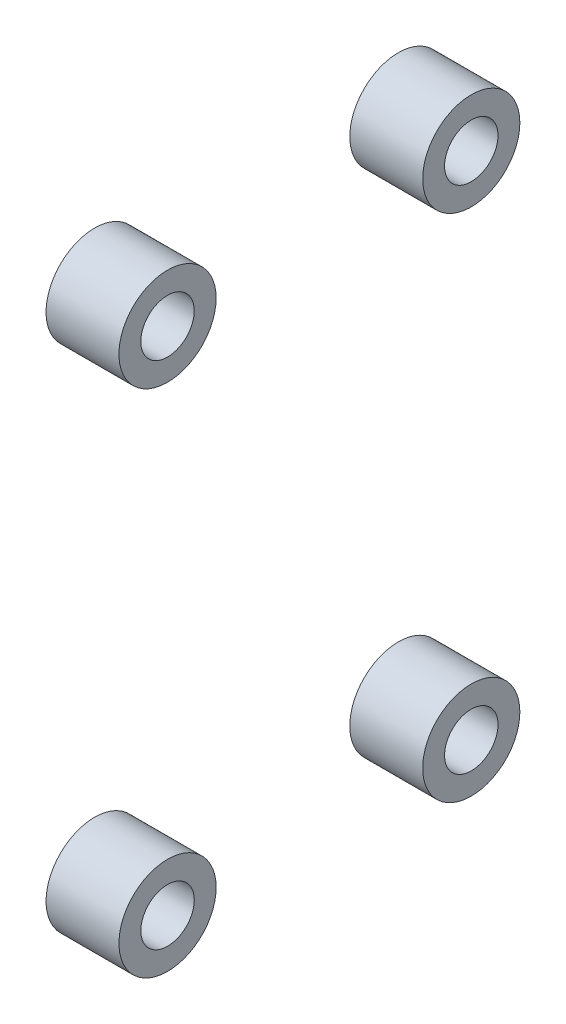
SolidWorks part; units mm, degrees
ref_plane "Alzado" through (0, 0, 0) normal (0, 0, 1) x (1, 0, 0)
ref_plane "Planta" through (0, 0, 0) normal (0, 1, 0) x (1, 0, 0)
ref_plane "Vista lateral" through (0, 0, 0) normal (1, 0, 0) x (0, 0, -1)
ref_plane "Plano1" through (-15.9, 0, 0) normal (1, 0, 0) x (0, 0, -1)
sketch "Croquis1" plane through (-15.9, 0, 0) normal (1, 0, 0) x (0, 0, -1)
  circle A0 centre (-97, -10.5) radius 2
  circle A1 centre (-84.5, -10.5) radius 2
  circle A2 centre (-97, 10.5) radius 2
  circle A3 centre (-84.5, 10.5) radius 2
extrude "Saliente-Extruir1" add sketch "Croquis1" along normal blind 3
ref_plane "Plano2" through (-16.9, 0, 0) normal (1, 0, 0) x (0, 0, -1)
sketch "Croquis2" plane through (-16.9, 0, 0) normal (1, 0, 0) x (0, 0, -1)
  circle A0 centre (-97, -10.5) radius 1.1
  circle A1 centre (-84.5, -10.5) radius 1.1
  circle A2 centre (-97, 10.5) radius 1.1
  circle A3 centre (-84.5, 10.5) radius 1.1
extrude "Cortar-Extruir1" cut sketch "Croquis2" along normal blind 5
